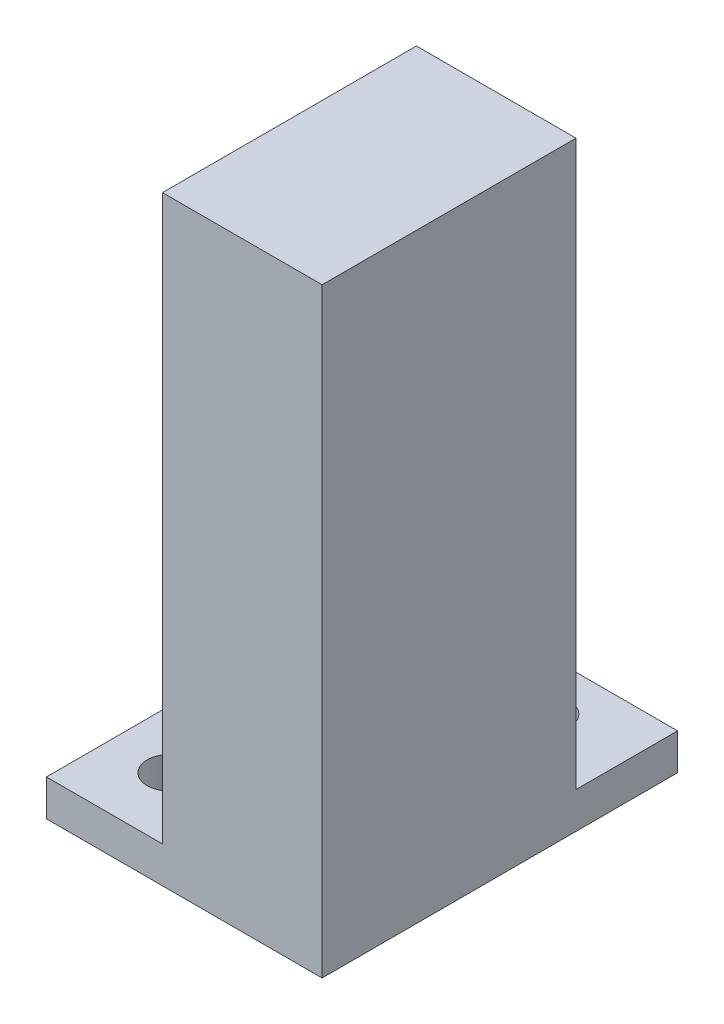
SolidWorks part; units mm, degrees
ref_plane "Front Plane" through (0, 0, 0) normal (0, 0, 1) x (1, 0, 0)
ref_plane "Top Plane" through (0, 0, 0) normal (0, 1, 0) x (1, 0, 0)
ref_plane "Right Plane" through (0, 0, 0) normal (1, 0, 0) x (0, 0, -1)
sketch "Sketch1" plane through (0, 0, 0) normal (0, 0, 1) x (1, 0, 0)
  line L0 (-11, 49.2197) -> (-11, -33.5303)
  line L2 (11, 49.2197) -> (11, -33.5303)
  line L3 (11, 49.2197) -> (-11, 49.2197)
  line L5 (-11, -33.5303) -> (11, -33.5303)
  circle A0 centre (0, 35.7197) radius 3.1
  circle A1 centre (0, 7.7197) radius 3.1
  dimension "D1" = 13.5
  dimension "D2" = 28
  dimension "D3" = 82.75
  dimension "D5" = 11
extrude "Boss-Extrude1" add sketch "Sketch1" along normal blind 30
sketch "Sketch2" plane through (0, 0, 30) normal (0, 0, 1) x (1, 0, 0)
  line L0 (-11, -33.5303) -> (11, -33.5303) construction
  line L2 (11, 49.2197) -> (-11, 49.2197) construction
  line L4 (-11, -33.5303) -> (11, -33.5303)
  line L5 (11, -33.5303) -> (11, 49.2197)
  line L6 (11, 49.2197) -> (-11, 49.2197)
  line L7 (-11, 49.2197) -> (-11, -33.5303)
extrude "Boss-Extrude2" add sketch "Sketch2" along normal blind 5
sketch "Sketch3" plane through (0, -33.5303, 0) normal (0, -1, 0) x (1, 0, 0)
  line L0 (-11, 0) -> (-27, 0)
  line L1 (-27, 0) -> (-27, 35)
  line L2 (-27, 35) -> (-11, 35)
  line L3 (-11, 0) -> (-11, -14)
  line L4 (-11, -14) -> (11, -14)
  line L5 (11, -14) -> (11, 0)
  line L6 (-11, 0) -> (11, 0)
  line L7 (-11, 0) -> (-11, 35)
  circle A0 centre (-19, 9) radius 3.1
  circle A1 centre (-19, 26) radius 3.1
  circle A2 centre (0, -7) radius 3.1
  line M4 (-11, 0) -> (11, 0)
  line M7 (-11, 35) -> (-11, 0)
  dimension "D1" = 6.2
  dimension "D2" = 6.2
  dimension "D3" = 9
  dimension "D4" = 9
  dimension "D6" = 6.2
  dimension "D7" = 11
  dimension "D5" = 14
extrude "Boss-Extrude3" add sketch "Sketch3" against normal blind 5 contours L2 L1 L0 A1 A0 M7 | L4 L5 L3 A2 M4
sketch "Sketch4" plane through (11, 0, 0) normal (1, 0, 0) x (0, 0, -1)
  line L6 (-35, -33.5303) -> (14, -33.5303)
  line L7 (14, -33.5303) -> (14, -28.5303)
  line L8 (14, -28.5303) -> (0, -28.5303)
  line L9 (0, -28.5303) -> (0, 49.2197)
  line L10 (0, 49.2197) -> (-35, 49.2197)
  line L11 (-35, 49.2197) -> (-35, -33.5303)
  line L12 (-35, -33.5303) -> (14, -33.5303)
  line L13 (14, -33.5303) -> (14, -28.5303)
  line L14 (14, -28.5303) -> (0, -28.5303)
  line L15 (0, -28.5303) -> (0, 49.2197)
  line L16 (0, 49.2197) -> (-35, 49.2197)
  line L17 (-35, 49.2197) -> (-35, -33.5303)
  dimension "D1" = 0
extrude "Boss-Extrude4" [suppressed] add sketch "Sketch4" along normal blind 2.5
sketch "Sketch5" plane through (0, 0, 30) normal (0, 0, -1) x (-1, 0, 0)
  circle A1 centre (0, 7.7197) radius 3.1
  circle A2 centre (0, 7.7197) radius 3.1
  circle A3 centre (0, 35.7197) radius 3.1
  circle A4 centre (0, 35.7197) radius 3.1
  dimension "D1" = 0
  dimension "D2" = 0
extrude "Boss-Extrude5" add sketch "Sketch5" along normal blind 15
